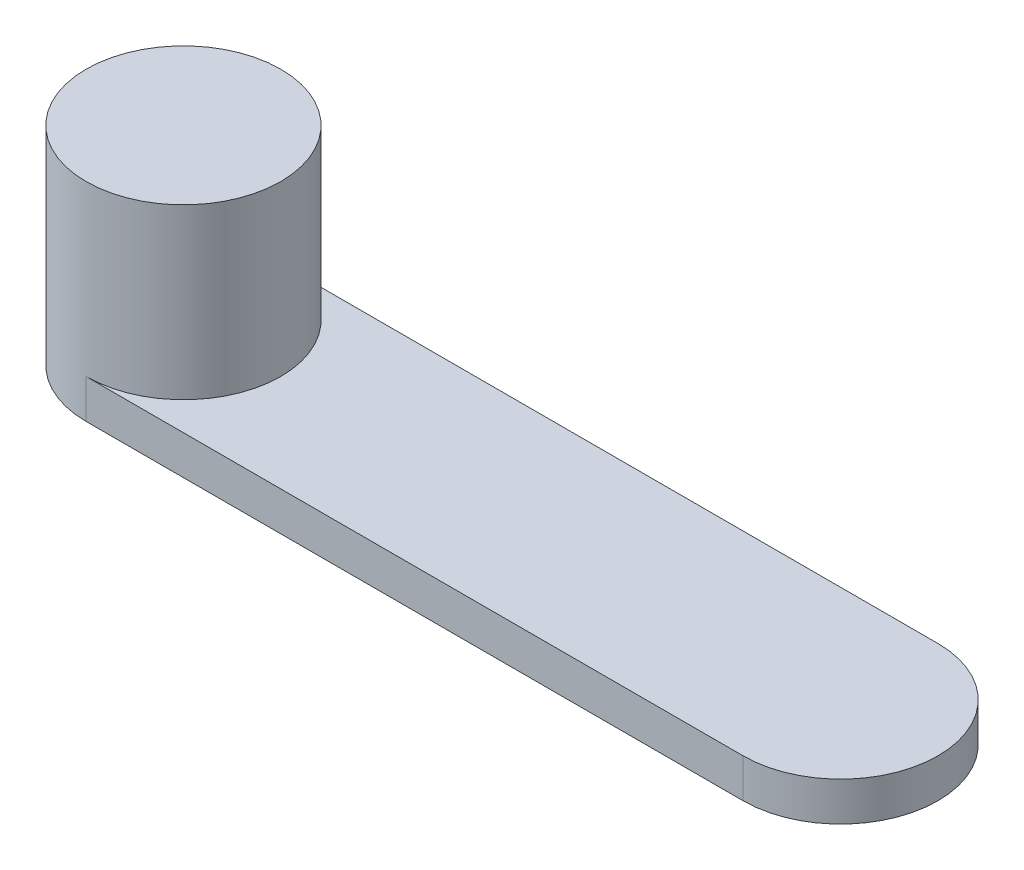
SolidWorks part; units mm, degrees
ref_plane "前视基准面" through (0, 0, 0) normal (0, 0, 1) x (1, 0, 0)
ref_plane "上视基准面" through (0, 0, 0) normal (0, 1, 0) x (1, 0, 0)
ref_plane "右视基准面" through (0, 0, 0) normal (1, 0, 0) x (0, 0, -1)
other "质心 (COM)"
sketch "草图1" plane through (0, 0, 0) normal (0, 1, 0) x (1, 0, 0)
  line L0 (67.5, 0) -> (-67.5, 0) construction
  line L1 (67.5, -20) -> (-67.5, -20)
  line L2 (67.5, 20) -> (-67.5, 20)
  arc A0 (67.5, -20) -> (67.5, 20) centre (67.5, 0) ccw
  arc A1 (-67.5, 20) -> (-67.5, -20) centre (-67.5, 0) ccw
  point P2 (0, 0)
  dimension "D1" = 20
  dimension "D2" = 135
extrude "凸台-拉伸1" add sketch "草图1" along normal blind 8
sketch "草图3" plane through (0, 8, 0) normal (0, 1, 0) x (1, 0, 0)
  arc A0 (-67.5, 20) -> (-67.5, -20) centre (-67.5, 0) ccw construction
  arc A1 (-67.5, 20) -> (-67.5, -20) centre (-67.5, 0) ccw construction
  circle A2 centre (-67.5, 0) radius 20
extrude "凸台-拉伸2" add sketch "草图3" along normal blind 34.68
